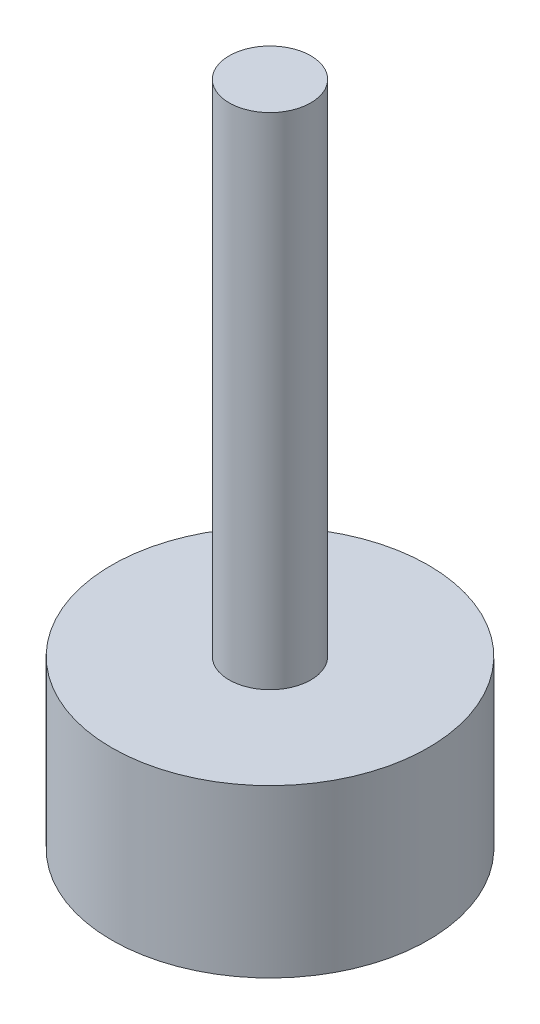
SolidWorks part; units mm, degrees
ref_plane "Front Plane" through (0, 0, 0) normal (0, 0, 1) x (1, 0, 0)
ref_plane "Top Plane" through (0, 0, 0) normal (0, 1, 0) x (1, 0, 0)
ref_plane "Right Plane" through (0, 0, 0) normal (1, 0, 0) x (0, 0, -1)
sketch "Sketch1" plane through (0, 0, 0) normal (0, 1, 0) x (1, 0, 0)
  circle A0 centre (0, 0) radius 12.065
  dimension "D1" = 24.13
extrude "Boss-Extrude1" add sketch "Sketch1" along normal blind 12.7
sketch "Sketch2" plane through (0, 12.7, 0) normal (0, 1, 0) x (1, 0, 0)
  circle A0 centre (0, 0) radius 3.1115
  dimension "D1" = 6.223
extrude "Boss-Extrude2" add sketch "Sketch2" along normal blind 38.1
